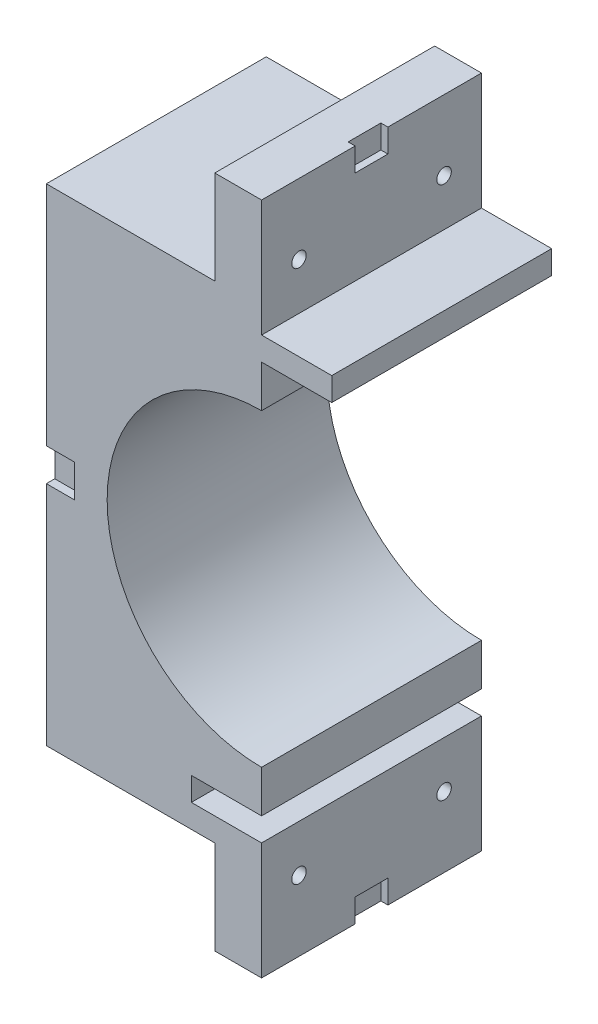
SolidWorks part; units mm, degrees
ref_plane "前视基准面" through (0, 0, 0) normal (0, 0, 1) x (1, 0, 0)
ref_plane "上视基准面" through (0, 0, 0) normal (0, 1, 0) x (1, 0, 0)
ref_plane "右视基准面" through (0, 0, 0) normal (1, 0, 0) x (0, 0, -1)
other "Configuration Table"
sketch "草图1" plane through (0, 0, 0) normal (0, 0, 1) x (1, 0, 0)
  line L0 (0, 33) -> (0, 52)
  line L1 (0, 52) -> (-46, 52)
  line L2 (-46, 52) -> (-46, -52)
  line L4 (0, -52) -> (0, -33)
  line L11 (-46, -52) -> (0, -52)
  arc A0 (0, 33) -> (0, -33) centre (0, 0) ccw
  dimension "D1" = 66
  dimension "D2" = 19
  dimension "D3" = 19
  dimension "D4" = 46
  dimension "D5" = 104
extrude "凸台-拉伸1" add sketch "草图1" along normal blind 47
ref_plane "基准面1" through (-10, 0, 0) normal (1, 0, 0) x (0, 0, -1)
sketch "草图2" plane through (-10, 0, 0) normal (1, 0, 0) x (0, 0, -1)
  line L20 (-47, 52) -> (0, 52)
  line L21 (-47, 52) -> (-47, 72)
  line L22 (-47, 72) -> (0, 72)
  line L23 (0, 52) -> (0, 72)
  dimension "D1" = 20
extrude "凸台-拉伸2" add sketch "草图2" along normal blind 10
sketch "草图5" plane through (-10, 0, 0) normal (1, 0, 0) x (0, 0, -1)
  line L8 (-47, -52) -> (0, -52)
  line L9 (-47, -52) -> (-47, -72)
  line L10 (-47, -72) -> (0, -72)
  line L11 (0, -52) -> (0, -72)
  dimension "D1" = 20
extrude "凸台-拉伸5" add sketch "草图5" along normal blind 10
sketch "草图6" plane through (0, 0, 47) normal (0, 0, 1) x (1, 0, 0)
  line L0 (0, -72) -> (0, -33) construction
  line L1 (0, -42) -> (-15, -42)
  line L2 (0, -42) -> (0, -47)
  line L3 (0, -47) -> (-15, -47)
  line L4 (-15, -42) -> (-15, -47)
  line L5 (-46, -52) -> (-10, -52) construction
  dimension "D1" = 5
  dimension "D2" = 5
  dimension "D3" = 15
extrude "切除-拉伸1" cut sketch "草图6" against normal through all
sketch "草图7" plane through (0, 0, 47) normal (0, 0, 1) x (1, 0, 0)
  line L0 (0, 33) -> (0, 72) construction
  line L1 (0, 47) -> (15, 47)
  line L2 (0, 47) -> (0, 42)
  line L3 (0, 42) -> (15, 42)
  line L4 (15, 47) -> (15, 42)
  line L5 (-10, 52) -> (-46, 52) construction
  dimension "D1" = 5
  dimension "D2" = 15
  dimension "D3" = 5
extrude "凸台-拉伸6" add sketch "草图7" against normal through all
sketch "草图8" plane through (0, -72, 0) normal (0, -1, 0) x (1, 0, 0)
  line L0 (0, 47) -> (0, 0) construction
  line L1 (0, 27) -> (-1.5, 27)
  line L2 (0, 27) -> (0, 20)
  line L3 (0, 20) -> (-1.5, 20)
  line L4 (-1.5, 27) -> (-1.5, 20)
  line L5 (0, 47) -> (-10, 47) construction
  line L6 (0, 0) -> (-10, 0) construction
  dimension "D1" = 20
  dimension "D2" = 20
  dimension "D3" = 1.5
extrude "切除-拉伸2" cut sketch "草图8" against normal blind 5
sketch "草图10" plane through (0, 0, 0) normal (1, 0, 0) x (0, 0, -1)
  line L0 (-47, -72) -> (-27, -72) construction
  line L1 (-20, -72) -> (0, -72) construction
  line L2 (-47, -72) -> (-47, -47) construction
  line L3 (0, -72) -> (0, -47) construction
  circle A0 centre (-39, -57) radius 1.55
  circle A1 centre (-8, -57) radius 1.55
  dimension "D5" = 3.1
  dimension "D6" = 3.1
  dimension "D1" = 15
  dimension "D2" = 15
  dimension "D3" = 8
  dimension "D4" = 8
extrude "切除-拉伸4" cut sketch "草图10" against normal through all
sketch "草图12" plane through (-10, 0, 0) normal (-1, 0, 0) x (0, 0, 1)
  line L0 (0, 72) -> (47, 72) construction
  line L1 (0, 52) -> (0, 72) construction
  line L2 (47, 72) -> (47, 52) construction
  circle A0 centre (8, 57) radius 1.55
  circle A1 centre (39, 57) radius 1.55
  dimension "D5" = 3.1
  dimension "D6" = 3.1
  dimension "D1" = 15
  dimension "D2" = 15
  dimension "D3" = 8
  dimension "D4" = 8
extrude "切除-拉伸5" cut sketch "草图12" against normal through all
sketch "草图13" plane through (0, 72, 0) normal (0, 1, 0) x (1, 0, 0)
  line L4 (-1.5, -27) -> (0, -27)
  line L5 (-1.5, -20) -> (-1.5, -27)
  line L6 (0, -20) -> (-1.5, -20)
  line L7 (0, -27) -> (0, -20)
  line L8 (-1.5, -27) -> (0, -27)
  line L9 (-1.5, -20) -> (-1.5, -27)
  line L10 (0, -20) -> (-1.5, -20)
  line L11 (0, -27) -> (0, -20)
  dimension "D1" = 0
extrude "切除-拉伸6" cut sketch "草图13" against normal blind 5
sketch "草图14" plane through (-46, 0, 0) normal (-1, 0, 0) x (0, 0, 1)
  line L0 (47, 52) -> (47, -52) construction
  line L1 (47, -3.5) -> (45.2, -3.5)
  line L2 (47, -3.5) -> (47, 3.5)
  line L3 (47, 3.5) -> (45.2, 3.5)
  line L4 (45.2, -3.5) -> (45.2, 3.5)
  line L5 (47, -52) -> (0, -52) construction
  dimension "D1" = 48.5
  dimension "D2" = 7
  dimension "D3" = 1.8
extrude "切除-拉伸7" cut sketch "草图14" against normal blind 6
